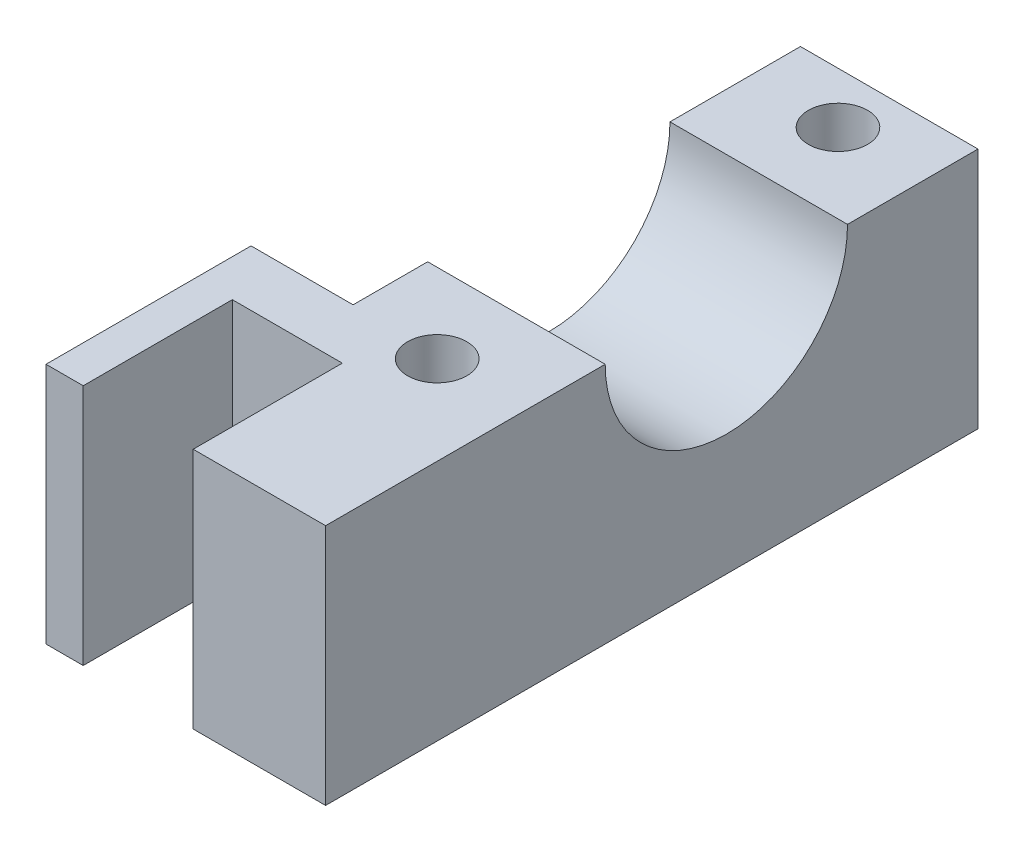
SolidWorks part; units mm, degrees
ref_plane "Front Plane" through (0, 0, 0) normal (0, 0, 1) x (1, 0, 0)
ref_plane "Top Plane" through (0, 0, 0) normal (0, 1, 0) x (1, 0, 0)
ref_plane "Right Plane" through (0, 0, 0) normal (1, 0, 0) x (0, 0, -1)
sketch "Sketch1" plane through (0, 0, 0) normal (1, 0, 0) x (0, 0, -1)
  line L0 (6.5, 0) -> (13.5, 0)
  line L1 (-13.5, 0) -> (-6.5, 0)
  line L2 (-13.5, 0) -> (-13.5, -13)
  line L3 (-13.5, -13) -> (13.5, -13)
  line L4 (13.5, 0) -> (13.5, -13)
  arc A0 (-6.5, 0) -> (6.5, 0) centre (0, 0) ccw
  dimension "D1" = 13
  dimension "D3" = 13
  dimension "D4" = 13.5
  dimension "D2" = 27
  dimension "D5" = 0
extrude "Boss-Extrude1" add sketch "Sketch1" along normal blind 15
sketch "Sketch4" plane through (0, -13, 0) normal (0, -1, 0) x (1, 0, 0)
  line L3 (15, -13.5) -> (0, -13.5) construction
  line L5 (15, 13.5) -> (15, -13.5) construction
  line L6 (15, 13.5) -> (15, -13.5) construction
  line L7 (15, 13.5) -> (0, 13.5) construction
  circle A0 centre (10.2375, -10.75) radius 1.5875
  circle A1 centre (10.2375, 10.75) radius 1.5875
  dimension "D1" = 3.175
  dimension "D4" = 3.175
  dimension "D3" = 2.75
  dimension "D2" = 4.7625
  dimension "D5" = 4.7625
  dimension "D6" = 2.75
extrude "Cut-Extrude2" cut sketch "Sketch4" against normal through all
sketch "Sketch6" plane through (0, 0, 13.5) normal (0, 0, 1) x (1, 0, 0)
  line L0 (7.8968, 0) -> (15, 0)
  line L1 (0, 0) -> (1.9968, 0)
  line L2 (0, 0) -> (0, -13)
  line L3 (0, -13) -> (1.9968, -13)
  line L4 (15, 0) -> (15, -13)
  line L6 (1.9968, -13) -> (1.9968, 0)
  line L7 (7.8968, -13) -> (15, -13)
  line L8 (7.8968, -13) -> (7.8968, 0)
  dimension "D1" = 5.9
extrude "Boss-Extrude2" add sketch "Sketch6" along normal blind 8
sketch "Sketch7" plane through (0, 0, 0) normal (0, 1, 0) x (1, 0, 0)
  line L0 (7.8968, -13.5) -> (1.9968, -13.5) construction
  line L1 (0, 13.5) -> (5.475, 13.5)
  line L2 (0, 13.5) -> (0, -10.5)
  line L3 (0, -10.5) -> (5.475, -10.5)
  line L4 (5.475, 13.5) -> (5.475, -10.5)
  line L5 (15, 13.5) -> (15, 6.5) construction
  dimension "D1" = 3
  dimension "D2" = 9.525
extrude "Cut-Extrude3" cut sketch "Sketch7" against normal through all
equation "\"D4@Sketch1\"=\"D2@Sketch1\"/2"
equation "\"D4@Sketch4\"=\"D1@Sketch4\""
equation "\"D2@Sketch4\"=\"D5@Sketch4\""
equation "\"D6@Sketch4\"=\"D3@Sketch4\""
